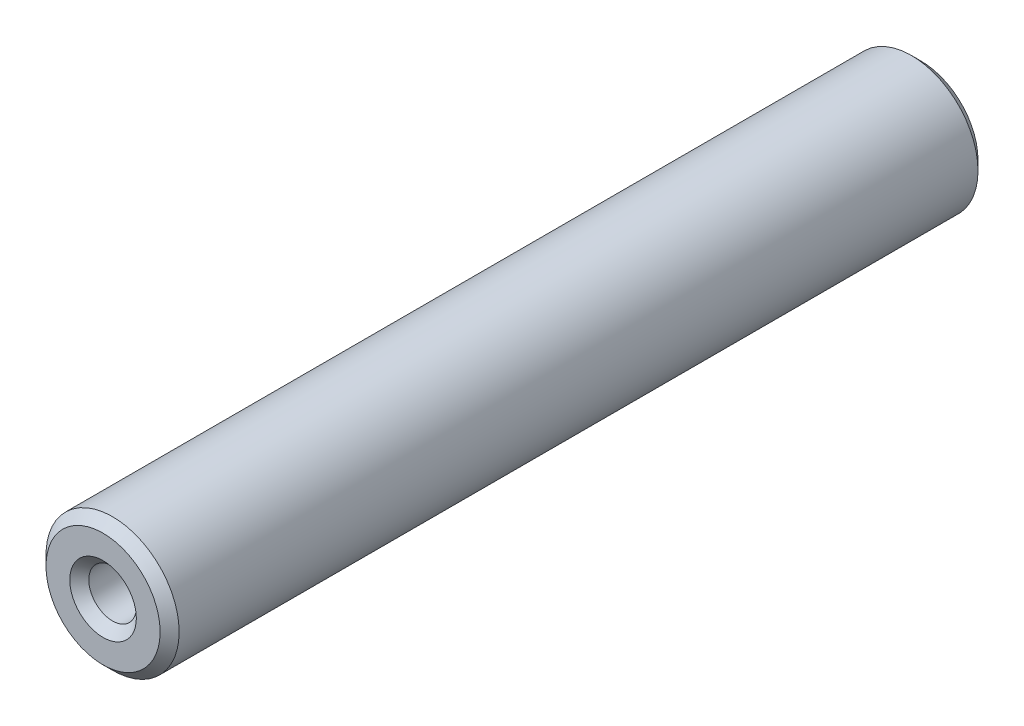
SolidWorks part; units mm, degrees
material "7075-T6, Plate (SS)"
ref_plane "前视基准面" through (0, 0, 0) normal (0, 0, 1) x (1, 0, 0)
ref_plane "上视基准面" through (0, 0, 0) normal (0, 1, 0) x (1, 0, 0)
ref_plane "右视基准面" through (0, 0, 0) normal (1, 0, 0) x (0, 0, -1)
sketch "草图1" plane through (0, 0, 0) normal (0, 0, 1) x (1, 0, 0)
  circle A0 centre (0, 0) radius 3.5
  dimension "D1" = 7
extrude "拉伸1" add sketch "草图1" along normal mid plane 43
hole_wizard "M3 螺纹孔1" positions "3D草图1" profile "草图2" tap size "M3" standard "GB"
sketch3d "3D草图1"
  line L0 (0, 0, 21.5) -> (0, 0, -21.5) construction
  circle A0 centre (0, 0, 21.5) radius 3.5 construction
  point P0 (0, 0, 21.5)
  point P2 (0, 0, -21.5)
  point P10 (0, 0, 25)
sketch "草图2" plane through (0, 0, 21.5) normal (1, 0, 0) x (0, -1, 0)
  line L0 (0, 0) -> (0, 8.2511)
  line L1 (0, 8.2511) -> (1.25, 7.5)
  line L2 (1.25, 7.5) -> (1.25, 0)
  line L5 (1.25, 0) -> (0, 0)
  line L10 (0, 8.2511) -> (-1.25, 7.5) construction
  line L11 (0, -6.35) -> (0, 107.95) construction
  dimension "螺纹孔钻头直径" = 2.5
  dimension "螺纹孔钻头深度" = 7.5
  dimension "导头角度" = 118
cosmetic thread "孔螺蚊线1" parameters "D1"=6, "D2"=3
cosmetic thread "孔螺蚊线2" parameters "D1"=6, "D2"=3
chamfer "倒角1" distance 0.5 angle 45 4 edges at (3.5, 0, -21.5) (-1.25, 0, -21.5) (3.5, 0, 21.5) (1.25, 0, 21.5)
